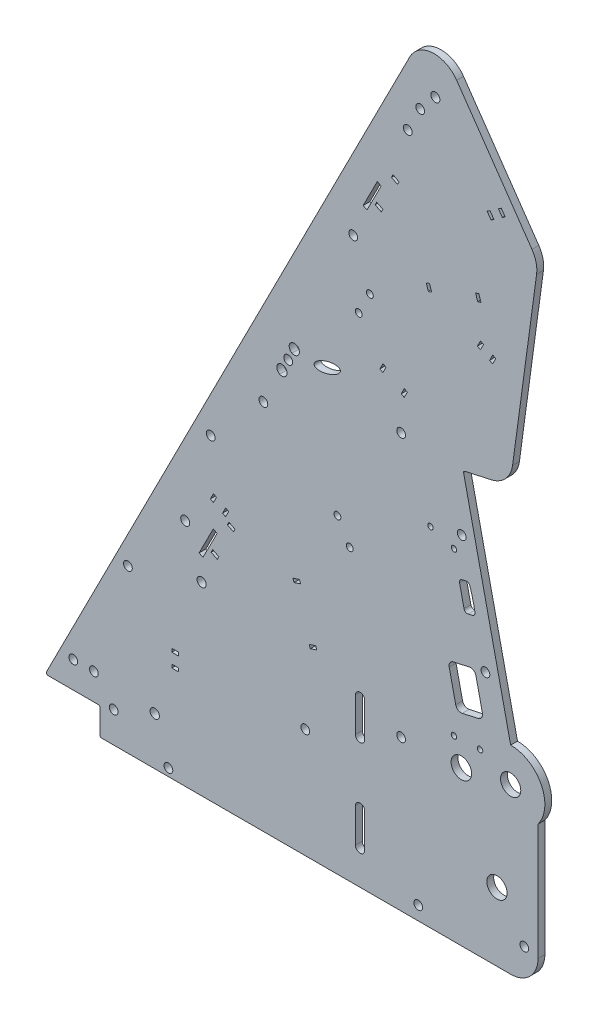
SolidWorks part; units mm, degrees
other "Markup1"
sketch "Sketch5"
ref_plane "Front Plane" through (0, 0, 0) normal (0, 0, 1) x (1, 0, 0)
ref_plane "Top Plane" through (0, 0, 0) normal (0, 1, 0) x (1, 0, 0)
ref_plane "Right Plane" through (0, 0, 0) normal (1, 0, 0) x (0, 0, -1)
sketch "Sketch1" plane through (0, 0, 0) normal (0, 0, 1) x (1, 0, 0)
  line L1 (228.6, -12.7) -> (228.6, 53.975)
  line L2 (178.7547, 351.4131) -> (0, 0)
  line L3 (228.6, 279.4) -> (178.7547, 351.4131)
  line L5 (0, 0) -> (25.4, 0)
  line L6 (25.4, 0) -> (25.4, -12.7)
  line L7 (25.4, -12.7) -> (228.6, -12.7)
  line L9 (215.9, 79.375) -> (193.9097, 178.5667)
  line L10 (193.9097, 178.5667) -> (215.6079, 183.377)
  line L11 (215.6079, 183.377) -> (228.6, 279.4)
  arc A0 (228.6, 53.975) -> (215.9, 79.375) centre (215.9, 63.5) ccw
  dimension "D7" = 12.7
  dimension "D8" = 76.2
  dimension "D10" = 31.75
  dimension "D2" = 292.1
  dimension "D3" = 25.4
  dimension "D4" = 215.9
  dimension "D5" = 394.2644
  dimension "D6" = 203.2
  dimension "D9" = 63.039
  dimension "D11" = 101.6
  dimension "D12" = 12.5
  dimension "D13" = 22.225
extrude "Boss-Extrude1" add sketch "Sketch1" along normal blind 3.175
sketch "Sketch2" plane through (0, 0, 3.175) normal (0, 0, 1) x (1, 0, 0)
  line L0 (178.7547, 351.4131) -> (0, 0) construction
  line L1 (25.4, -12.7) -> (228.6, -12.7) construction
  line L2 (215.9, 79.375) -> (193.9097, 178.5667) construction
  line L3 (193.9097, 178.5667) -> (215.6079, 183.377) construction
  line L4 (215.9, 79.375) -> (193.9097, 178.5667) construction
  line L5 (64.9432, 94.0578) -> (72.5445, 73.1732) construction
  line L6 (64.9432, 94.0578) -> (89.8317, 94.0578) construction
  line L10 (228.6, -12.7) -> (228.6, 53.975) construction
  circle A0 centre (64.9432, 94.0578) radius 2.0955
  circle A1 centre (180.975, 322.1643) radius 2.0955
  circle A2 centre (72.5445, 73.1732) radius 2.0955
  circle A3 centre (193.2078, 152.3944) radius 2.032
  circle A4 centre (215.9, 63.5) radius 4.699
  circle A7 centre (173.0375, -6.35) radius 2.032
  circle A8 centre (204.203, 102.7985) radius 2.032
  circle A26 centre (209.55, 19.05) radius 4.699
  arc A30 (228.6, 53.975) -> (215.9, 79.375) centre (215.9, 63.5) ccw construction
  circle A31 centre (165.1, 179.3875) radius 2.032
  dimension "D3" = 4.191
  dimension "D5" = 4.191
  dimension "D9" = 4.191
  dimension "D20" = 9.398
  dimension "D23" = 9.398
  dimension "D18" = 4.064
  dimension "D26" = 4.064
  dimension "D14" = 4.064
  dimension "D2" = 15.24
  dimension "D6" = 15.24
  dimension "D7" = 22.225
  dimension "D21" = 44.45
  dimension "D22" = 6.35
  dimension "D19" = 160.3375
  dimension "D24" = 44.45
  dimension "D25" = 6.35
  dimension "D27" = 25.4
  dimension "D28" = 50.8
  dimension "D29" = 6.35
  dimension "D17" = 6.35
  dimension "D33" = 55.5625
  dimension "D15" = 114.3
  dimension "D4" = 180.975
  dimension "D8" = 70
extrude "Cut-Extrude1" cut sketch "Sketch2" against normal through all
sketch "Sketch7" plane through (0, 0, 3.175) normal (0, 0, 1) x (1, 0, 0)
  line L0 (146.05, 3.175) -> (146.05, 19.05) construction
  line L1 (143.891, 3.175) -> (143.891, 19.05)
  line L2 (148.209, 3.175) -> (148.209, 19.05)
  line L3 (146.05, 47.625) -> (146.05, 63.5) construction
  line L4 (143.891, 47.625) -> (143.891, 63.5)
  line L5 (148.209, 47.625) -> (148.209, 63.5)
  line L6 (25.4, -12.7) -> (228.6, -12.7) construction
  line L12 (228.6, -12.7) -> (228.6, 53.975) construction
  line L13 (25.4, -12.7) -> (228.6, -12.7) construction
  arc A0 (143.891, 3.175) -> (148.209, 3.175) centre (146.05, 3.175) ccw
  arc A1 (148.209, 19.05) -> (143.891, 19.05) centre (146.05, 19.05) ccw
  arc A2 (143.891, 47.625) -> (148.209, 47.625) centre (146.05, 47.625) ccw
  arc A3 (148.209, 63.5) -> (143.891, 63.5) centre (146.05, 63.5) ccw
  circle A8 centre (50.8, 9.525) radius 2.159
  point P2 (146.05, 11.1125)
  point P9 (146.05, 55.5625)
  dimension "D1" = 4.318
  dimension "D5" = 4.318
  dimension "D2" = 15.875
  dimension "D3" = 15.875
  dimension "D4" = 44.45
  dimension "D6" = 95.25
  dimension "D7" = 82.55
  dimension "D8" = 15.875
  dimension "D9" = 22.225
extrude "Cut-Extrude2" cut sketch "Sketch7" against normal through all
sketch "Sketch10" plane through (0, 0, 3.175) normal (0, 0, 1) x (1, 0, 0)
  circle A1 centre (165.1, 57.15) radius 2.032
  circle A2 centre (120.65, 38.1) radius 2.032
  circle A3 centre (13.0465, 12.3347) radius 2.032
  circle A4 centre (22.5715, 12.3347) radius 2.032
  circle A5 centre (38.3604, 62.564) radius 2.032
  dimension "D1" = 4.064
  dimension "D2" = 4.064
  dimension "D4" = 63.5
  dimension "D5" = 69.85
extrude "Cut-Extrude3" cut sketch "Sketch10" against normal up to next
fillet "Fillet1" radius 12.7 4 edges at (228.6, -12.7, 1.5875) (178.7547, 351.4131, 1.5875) (215.6079, 183.377, 1.5875) (228.6, 279.4, 1.5875)
fillet "Fillet2" radius 0.7937 4 edges at (25.4, -12.7, 1.5875) (25.4, 0, 1.5875) (193.9097, 178.5667, 1.5875) (0, 0, 1.5875)
sketch "Sketch12" plane through (0, 0, 3.175) normal (0, 0, 1) x (1, 0, 0)
  circle A0 centre (31.75, 1.5875) radius 2.032
  circle A1 centre (222.25, 1.5875) radius 2.032
  circle A2 centre (57.15, -9.2075) radius 2.032
  circle A3 centre (57.15, -9.2075) radius 2.286 construction
  dimension "D1" = 4.064
  dimension "D2" = 4.064
extrude "Cut-Extrude5" cut sketch "Sketch12" against normal through all
sketch "Sketch13" plane through (0, 0, 3.175) normal (0, 0, 1) x (1, 0, 0)
  line L2 (194.6847, 178.7385) -> (206.9592, 181.4597) construction
  line L5 (199.2434, 101.699) -> (189.6226, 145.0954) construction
  line L6 (189.6022, 69.9806) -> (201.7089, 70.5092) construction
  line L7 (186.8444, 98.9502) -> (199.2434, 101.699)
  line L8 (186.8444, 98.9502) -> (190.9676, 80.3518)
  line L9 (190.9676, 80.3518) -> (203.3665, 83.1006)
  line L10 (199.2434, 101.699) -> (203.3665, 83.1006)
  line L11 (189.6022, 69.9806) -> (190.9676, 80.3518) construction
  line L12 (201.7089, 70.5092) -> (203.3665, 83.1006) construction
  line L13 (215.9, 79.375) -> (194.0815, 177.7917) construction
  line L14 (178.7216, 148.5324) -> (189.6226, 145.0954) construction
  line L15 (195.1281, 134.9336) -> (193.4153, 134.5539)
  line L16 (192.209, 132.6604) -> (194.2706, 123.3612)
  line L17 (196.1641, 122.1549) -> (198.1091, 122.5861)
  line L18 (211.4332, 99.5233) -> (205.2337, 98.1489) construction
  line L19 (198.3765, 158.4184) -> (211.4332, 99.5233) construction
  circle A0 centre (189.6022, 69.9806) radius 1.27
  circle A1 centre (201.7089, 70.5092) radius 1.27
  circle A2 centre (178.7216, 148.5324) radius 1.27
  circle A3 centre (189.6226, 145.0954) radius 1.27
  arc A4 (199.3306, 124.402) -> (196.9796, 133.88) centre (134.9024, 113.4517) ccw
  arc A6 (199.4957, 103.5221) -> (189.2475, 149.7492) centre (134.9024, 113.4517) ccw construction
  arc A7 (195.1281, 134.9336) -> (196.9796, 133.88) centre (195.4717, 133.3837) cw
  arc A8 (198.1091, 122.5861) -> (199.3306, 124.402) centre (197.7655, 124.136) ccw
  arc A9 (194.2706, 123.3612) -> (196.1641, 122.1549) centre (195.8205, 123.7048) ccw
  arc A10 (193.4153, 134.5539) -> (192.209, 132.6604) centre (193.7589, 133.004) ccw
  point P26 (208.3335, 98.8361)
  point P31 (196.515, 135.2411)
  point P36 (194.6142, 121.8113)
  point P39 (191.8654, 134.2103)
  dimension "D7" = 2.54
  dimension "D16" = 1.5875
  dimension "D2" = 11.43
  dimension "D3" = 76.2
  dimension "D4" = 12.7
  dimension "D5" = 19.05
  dimension "D6" = 120
  dimension "D8" = 110
  dimension "D9" = 80
  dimension "D10" = 12.7
  dimension "D11" = 44.45
  dimension "D12" = 11.43
  dimension "D13" = 12.7
  dimension "D14" = 4.7625
  dimension "D15" = 38.1
extrude "Cut-Extrude6" cut sketch "Sketch13" against normal through all both and the other way through all
sketch "Sketch14" plane through (0, 0, 3.175) normal (0, 0, 1) x (1, 0, 0)
  line L0 (26.1937, -12.7) -> (215.9, -12.7) construction
  line L1 (228.6, 0) -> (228.6, 53.975) construction
  line L2 (112.7125, 182.5625) -> (101.1964, 159.9231) construction
  line L3 (169.1053, 332.4434) -> (0.5868, 1.1536) construction
  line L4 (112.7125, 182.5625) -> (136.864, 190.4279) construction
  line L5 (147.4827, 261.9243) -> (154.0469, 274.8287)
  line L6 (147.4827, 261.9243) -> (149.2654, 261.0175)
  line L7 (154.0469, 274.8287) -> (155.8295, 273.922)
  line L8 (149.2654, 261.0175) -> (155.8295, 273.922)
  line L9 (169.1053, 332.4434) -> (0.5868, 1.1536) construction
  line L10 (160.5905, 279.7801) -> (161.3102, 281.1951)
  line L11 (160.5905, 279.7801) -> (163.4204, 278.3406)
  line L12 (161.3102, 281.1951) -> (164.1402, 279.7556)
  line L13 (163.4204, 278.3406) -> (164.1402, 279.7556)
  line L14 (153.7897, 266.4104) -> (156.6196, 264.9709)
  line L15 (153.7897, 266.4104) -> (153.0699, 264.9954)
  line L16 (156.6196, 264.9709) -> (155.8998, 263.5559)
  line L17 (153.0699, 264.9954) -> (155.8998, 263.5559)
  line L19 (178.2697, 245.9923) -> (179.2404, 242.9693)
  line L20 (178.2697, 245.9923) -> (176.7582, 245.5069)
  line L21 (179.2404, 242.9693) -> (177.7289, 242.4839)
  line L22 (176.7582, 245.5069) -> (177.7289, 242.4839)
  line L24 (200.6096, 249.8308) -> (199.639, 252.8538)
  line L25 (200.6096, 249.8308) -> (202.1211, 250.3161)
  line L26 (199.639, 252.8538) -> (201.1505, 253.3391)
  line L27 (202.1211, 250.3161) -> (201.1505, 253.3391)
  line L34 (77.9534, 97.2255) -> (79.736, 96.3187)
  line L47 (77.9534, 97.2255) -> (71.3892, 84.3211)
  line L56 (79.736, 96.3187) -> (73.1718, 83.4143)
  line L57 (71.3892, 84.3211) -> (73.1718, 83.4143)
  line L58 (85.2167, 103.5918) -> (84.497, 102.1769)
  line L59 (85.2167, 103.5918) -> (88.0466, 102.1523)
  line L60 (84.497, 102.1769) -> (87.3269, 100.7374)
  line L61 (88.0466, 102.1523) -> (87.3269, 100.7374)
  line L62 (156.643, 199.3999) -> (158.0826, 202.2298)
  line L63 (156.643, 199.3999) -> (155.2281, 200.1197)
  line L64 (158.0826, 202.2298) -> (156.6676, 202.9496)
  line L65 (155.2281, 200.1197) -> (156.6676, 202.9496)
  line L66 (165.1328, 195.0814) -> (166.5723, 197.9113)
  line L67 (165.1328, 195.0814) -> (166.5478, 194.3617)
  line L68 (166.5723, 197.9113) -> (167.9873, 197.1916)
  line L69 (166.5478, 194.3617) -> (167.9873, 197.1916)
  line L78 (77.6961, 88.8072) -> (76.9764, 87.3922)
  line L79 (201.9154, 234.7497) -> (200.4759, 231.9198)
  line L80 (201.9154, 234.7497) -> (203.3303, 234.0299)
  line L81 (200.4759, 231.9198) -> (201.8908, 231.2)
  line L82 (203.3303, 234.0299) -> (201.8908, 231.2)
  line L83 (206.1357, 229.0407) -> (207.5752, 231.8707)
  line L84 (206.1357, 229.0407) -> (207.5507, 228.321)
  line L85 (207.5752, 231.8707) -> (208.9902, 231.1509)
  line L86 (207.5507, 228.321) -> (208.9902, 231.1509)
  line L88 (205.014, 288.3715) -> (206.821, 285.7609)
  line L89 (205.014, 288.3715) -> (206.3193, 289.275)
  line L90 (206.821, 285.7609) -> (208.1263, 286.6644)
  line L91 (206.3193, 289.275) -> (208.1263, 286.6644)
  line L92 (210.2352, 291.9855) -> (212.0422, 289.3749)
  line L93 (210.2352, 291.9855) -> (211.5405, 292.889)
  line L94 (212.0422, 289.3749) -> (213.3475, 290.2784)
  line L95 (211.5405, 292.889) -> (213.3475, 290.2784)
  line L96 (225.7968, 283.4499) -> (190.8675, 333.9133) construction
  line L97 (77.6961, 88.8072) -> (80.5261, 87.3677)
  line L98 (76.9764, 87.3922) -> (79.8063, 85.9527)
  line L99 (80.5261, 87.3677) -> (79.8063, 85.9527)
  line L100 (122.4534, 73.1037) -> (122.9512, 71.5963)
  line L101 (122.4534, 73.1037) -> (125.4682, 74.0993)
  line L102 (122.9512, 71.5963) -> (125.9661, 72.5919)
  line L103 (125.4682, 74.0993) -> (125.9661, 72.5919)
  line L104 (114.9173, 95.9228) -> (115.4151, 94.4154)
  line L105 (114.9173, 95.9228) -> (117.9322, 96.9185)
  line L106 (115.4151, 94.4154) -> (118.43, 95.411)
  line L107 (117.9322, 96.9185) -> (118.43, 95.411)
  line L108 (73.3338, 88.1438) -> (77.899, 97.1186) construction
  line L109 (75.1164, 87.2371) -> (79.6816, 96.2118) construction
  line L110 (76.2812, 89.5269) -> (86.5313, 84.313) construction
  line L111 (83.082, 102.8966) -> (93.3321, 97.6827) construction
  line L112 (121.934, 72.0825) -> (123.4755, 75.113) construction
  line L113 (127.9171, 72.8537) -> (123.4755, 75.113) construction
  line L114 (112.3753, 83.5081) -> (119.5388, 97.5909) construction
  line L115 (112.1491, 96.0767) -> (117.4079, 93.4017) construction
  line L116 (149.0052, 264.9173) -> (147.5544, 262.0651) construction
  line L117 (150.7878, 264.0106) -> (151.2099, 264.8403) construction
  line L118 (162.6248, 261.9162) -> (152.3747, 267.1302) construction
  line L119 (169.4256, 275.2859) -> (159.1755, 280.4999) construction
  line L120 (199.3876, 252.3597) -> (200.1584, 253.8749) construction
  line L121 (198.6169, 250.8445) -> (203.0585, 248.5852) construction
  line L122 (203.2698, 247.9167) -> (195.3067, 232.262) construction
  line L123 (180.2625, 244.9786) -> (175.0037, 247.6536) construction
  line L124 (178.1316, 240.7894) -> (185.2951, 254.8722) construction
  line L125 (190.7763, 226.1672) -> (185.5176, 228.8422) construction
  line L126 (58.7375, 39.6875) -> (61.9125, 39.6875)
  line L127 (58.7375, 39.6875) -> (58.7375, 38.1)
  line L128 (61.9125, 39.6875) -> (61.9125, 38.1)
  line L129 (58.7375, 38.1) -> (61.9125, 38.1)
  line L130 (58.7375, 33.3375) -> (61.9125, 33.3375)
  line L131 (58.7375, 33.3375) -> (58.7375, 31.75)
  line L132 (61.9125, 33.3375) -> (61.9125, 31.75)
  line L133 (58.7375, 31.75) -> (61.9125, 31.75)
  line L135 (78.0516, 111.4242) -> (76.6121, 108.5943)
  line L136 (78.0516, 111.4242) -> (79.4665, 110.7045)
  line L137 (76.6121, 108.5943) -> (78.027, 107.8745)
  line L138 (79.4665, 110.7045) -> (78.027, 107.8745)
  line L139 (82.2719, 105.7153) -> (83.7114, 108.5452)
  line L140 (82.2719, 105.7153) -> (83.6869, 104.9955)
  line L141 (83.7114, 108.5452) -> (85.1264, 107.8254)
  line L142 (83.6869, 104.9955) -> (85.1264, 107.8254)
  circle A0 centre (142.875, 247.65) radius 2.032
  circle A1 centre (112.7125, 182.5625) radius 2.032
  circle A2 centre (101.1964, 159.9231) radius 2.032
  circle A3 centre (150.594, 227.8985) radius 1.6 construction
  circle A4 centre (145.4254, 217.7376) radius 1.6 construction
  circle A5 centre (135.5457, 131.3585) radius 1.6 construction
  circle A6 centre (141.2457, 121.4859) radius 1.6 construction
  circle A7 centre (150.594, 227.8985) radius 1.6
  circle A8 centre (145.4254, 217.7376) radius 1.6
  circle A9 centre (135.5457, 131.3585) radius 1.6
  circle A10 centre (141.2457, 121.4859) radius 1.6
  arc A13 (0, 1.5875) -> (1.5875, 0) centre (1.5875, 1.5875) ccw construction
  ellipse E0 centre (109.8335, 176.9027) end of major axis (108.7539, 174.7802) minor radius 2.32 (108.7539, 174.7802) -> (110.9131, 179.0251) ccw construction
  ellipse E1 centre (109.8335, 176.9027) end of major axis (108.7539, 174.7802) minor radius 2.32 (108.7539, 174.7802) -> (110.9131, 179.0251) ccw
  ellipse E2 centre (130.8261, 188.4615) end of major axis (124.7883, 186.4952) minor radius 2.3812
  ellipse E3 centre (115.5915, 188.2223) end of major axis (114.5119, 186.0999) minor radius 2.32 (114.5119, 186.0999) -> (116.6711, 190.3448) ccw construction
  ellipse E4 centre (115.5915, 188.2223) end of major axis (114.5119, 186.0999) minor radius 2.32 (114.5119, 186.0999) -> (116.6711, 190.3448) ccw
  spline S0 degree 3 poles (1008.5248, 1963.4972) (-264.8214, -935.4578) (153.1817, 166.823) (110.3225, 179.2425) (110.1654, 179.2721) (109.6955, 179.3152) (109.3734, 179.2831) (108.9218, 179.1456) (108.7737, 179.0841) (108.4954, 178.9343) (108.365, 178.8464) (108.1219, 178.6442) (108.0097, 178.5297) (107.8134, 178.2839) (107.7278, 178.1512) (107.5834, 177.8672) (107.527, 177.7202) (107.4441, 177.4168) (107.4178, 177.2585) (107.3978, 176.9432) (107.4036, 176.7863) (107.4465, 176.4736) (107.4841, 176.3175) (107.5874, 176.0205) (107.6532, 175.8777) (107.8133, 175.6037) (107.9066, 175.4748) (116.556, 165.6387) (207.2632, 219.9049) (-1299.313, 1592.6452) knots -17.496982 -17.496982 -17.496982 -17.496982 0.0625 0.0625 0.125 0.125 0.25 0.25 0.3125 0.3125 0.375 0.375 0.4375 0.4375 0.5 0.5 0.5625 0.5625 0.625 0.625 0.6875 0.6875 0.75 0.75 0.8125 0.8125 0.875 0.875 6.02447 6.02447 6.02447 6.02447 only from (110.9131, 179.0251) to (108.7539, 174.7802) construction
  spline S1 degree 3 poles (110.9131, 179.0251) (110.7727, 179.0965) (110.6265, 179.1544) (110.3225, 179.2425) (110.1654, 179.2721) (109.6955, 179.3152) (109.3734, 179.2831) (108.9218, 179.1456) (108.7737, 179.0841) (108.4954, 178.9343) (108.365, 178.8464) (108.1219, 178.6442) (108.0097, 178.5297) (107.8134, 178.2839) (107.7278, 178.1512) (107.5834, 177.8672) (107.527, 177.7202) (107.4441, 177.4168) (107.4178, 177.2585) (107.3978, 176.9432) (107.4036, 176.7863) (107.4465, 176.4736) (107.4841, 176.3175) (107.5874, 176.0205) (107.6532, 175.8777) (107.8133, 175.6037) (107.9066, 175.4748) (108.2178, 175.121) (108.4736, 174.9228) (108.7539, 174.7802) knots 0 0 0 0 0.0625 0.0625 0.125 0.125 0.25 0.25 0.3125 0.3125 0.375 0.375 0.4375 0.4375 0.5 0.5 0.5625 0.5625 0.625 0.625 0.6875 0.6875 0.75 0.75 0.8125 0.8125 0.875 0.875 1 1 1 1
  spline S2 degree 3 poles (-1420.3275, 1467.1358) (182.122, 221.9776) (122.5576, 179.7991) (113.9875, 186.4501) (113.8729, 186.5577) (113.5583, 186.9155) (113.3974, 187.1901) (113.2413, 187.6401) (113.2046, 187.793) (113.1618, 188.1044) (113.1558, 188.2648) (113.176, 188.5797) (113.2018, 188.7347) (113.2848, 189.0394) (113.3426, 189.1891) (113.5563, 189.6095) (113.7586, 189.8627) (114.1212, 190.1647) (114.2542, 190.2544) (114.5324, 190.4041) (114.6775, 190.4645) (114.9798, 190.5567) (115.1369, 190.5882) (115.4499, 190.6199) (115.6074, 190.6207) (115.9244, 190.5918) (116.0795, 190.5623) (127.2954, 187.3224) (125.1094, 104.0575) (-1840.7764, 595.1392) knots -4.189038 -4.189038 -4.189038 -4.189038 0.0625 0.0625 0.125 0.125 0.25 0.25 0.3125 0.3125 0.375 0.375 0.4375 0.4375 0.5 0.5 0.625 0.625 0.6875 0.6875 0.75 0.75 0.8125 0.8125 0.875 0.875 0.9375 0.9375 5.517452 5.517452 5.517452 5.517452 only from (114.5119, 186.0999) to (116.6711, 190.3448) construction
  spline S3 degree 3 poles (114.5119, 186.0999) (114.3711, 186.1715) (114.2359, 186.2574) (113.9875, 186.4501) (113.8729, 186.5577) (113.5583, 186.9155) (113.3974, 187.1901) (113.2413, 187.6401) (113.2046, 187.793) (113.1618, 188.1044) (113.1558, 188.2648) (113.176, 188.5797) (113.2018, 188.7347) (113.2848, 189.0394) (113.3426, 189.1891) (113.5563, 189.6095) (113.7586, 189.8627) (114.1212, 190.1647) (114.2542, 190.2544) (114.5324, 190.4041) (114.6775, 190.4645) (114.9798, 190.5567) (115.1369, 190.5882) (115.4499, 190.6199) (115.6074, 190.6207) (115.9244, 190.5918) (116.0795, 190.5623) (116.3815, 190.4751) (116.53, 190.4166) (116.6711, 190.3448) knots 0 0 0 0 0.0625 0.0625 0.125 0.125 0.25 0.25 0.3125 0.3125 0.375 0.375 0.4375 0.4375 0.5 0.5 0.625 0.625 0.6875 0.6875 0.75 0.75 0.8125 0.8125 0.875 0.875 0.9375 0.9375 1 1 1 1
  point P179 (82.9794, 105.3554)
  dimension "D1" = 4.064
  dimension "D15" = 3.175
  dimension "D2" = 195.2625
  dimension "D3" = 115.8875
  dimension "D4" = 85.725
  dimension "D5" = 260.35
  dimension "D6" = 25.4
  dimension "D7" = 4.7625
  dimension "D8" = 12.7
  dimension "D9" = 19.05
  dimension "D10" = 45
  dimension "D11" = 6.858
  dimension "D12" = 7.62
  dimension "D13" = 3.175
  dimension "D14" = 1.5875
  dimension "D16" = 1.5875
  dimension "D17" = 1.5875
  dimension "D18" = 9.525
  dimension "D19" = 47.625
  dimension "D20" = 38.1
  dimension "D21" = 6.858
  dimension "D22" = 7.62
  dimension "D23" = 1.5875
  dimension "D24" = 3.175
  dimension "D25" = 1.5875
  dimension "D26" = 4.7625
  dimension "D27" = 4.7625
  dimension "D28" = 1.5875
  dimension "D29" = 3.175
  dimension "D30" = 9.525
  dimension "D31" = 4.7625
  dimension "D32" = 4.7625
  dimension "D33" = 1.5875
  dimension "D34" = 3.175
  dimension "D35" = 6.35
  dimension "D36" = 12.7
  dimension "D37" = 1.5875
  dimension "D38" = 3.175
  dimension "D39" = 9.525
  dimension "D40" = 57.15
  dimension "D41" = 44.45
  dimension "D42" = 1.5875
  dimension "D43" = 4.7625
  dimension "D44" = 3.175
extrude "Cut-Extrude7" cut sketch "Sketch14" against normal through all
sketch "Sketch15" plane through (0, 0, 3.175) normal (0, 0, 1) x (1, 0, 0)
  line L0 (169.1053, 332.4434) -> (0.5868, 1.1536) construction
  circle A0 centre (76.7868, 134.1481) radius 2.032
  circle A1 centre (173.9472, 313.9507) radius 2.032
  circle A2 centre (168.1892, 302.631) radius 2.032
  circle A3 centre (173.9472, 313.9507) radius 1.905 construction
  circle A4 centre (168.1892, 302.631) radius 1.905 construction
  dimension "D1" = 4.064
  dimension "D4" = 4.064
  dimension "D2" = 7.62
  dimension "D3" = 76.2
extrude "Cut-Extrude8" cut sketch "Sketch15" against normal through all
fillet "Fillet3" radius 2.54 4 edges at (199.2434, 101.699, 1.5875) (186.8444, 98.9502, 1.5875) (190.9676, 80.3518, 1.5875) (203.3665, 83.1006, 1.5875)
sketch "Sketch16" plane through (0, 0, 3.175) normal (0, 0, 1) x (1, 0, 0)
  line L0 (228.6, 0) -> (228.6, 53.975) construction
  line L1 (26.1937, -12.7) -> (215.9, -12.7) construction
  circle A0 centre (193.04, 58.801) radius 4.7625
  dimension "D1" = 9.525
  dimension "D2" = 35.56
  dimension "D3" = 71.501
extrude "Cut-Extrude9" cut sketch "Sketch16" against normal through all
equation "\"D6@Sketch2\"=\"D2@Sketch2\""
